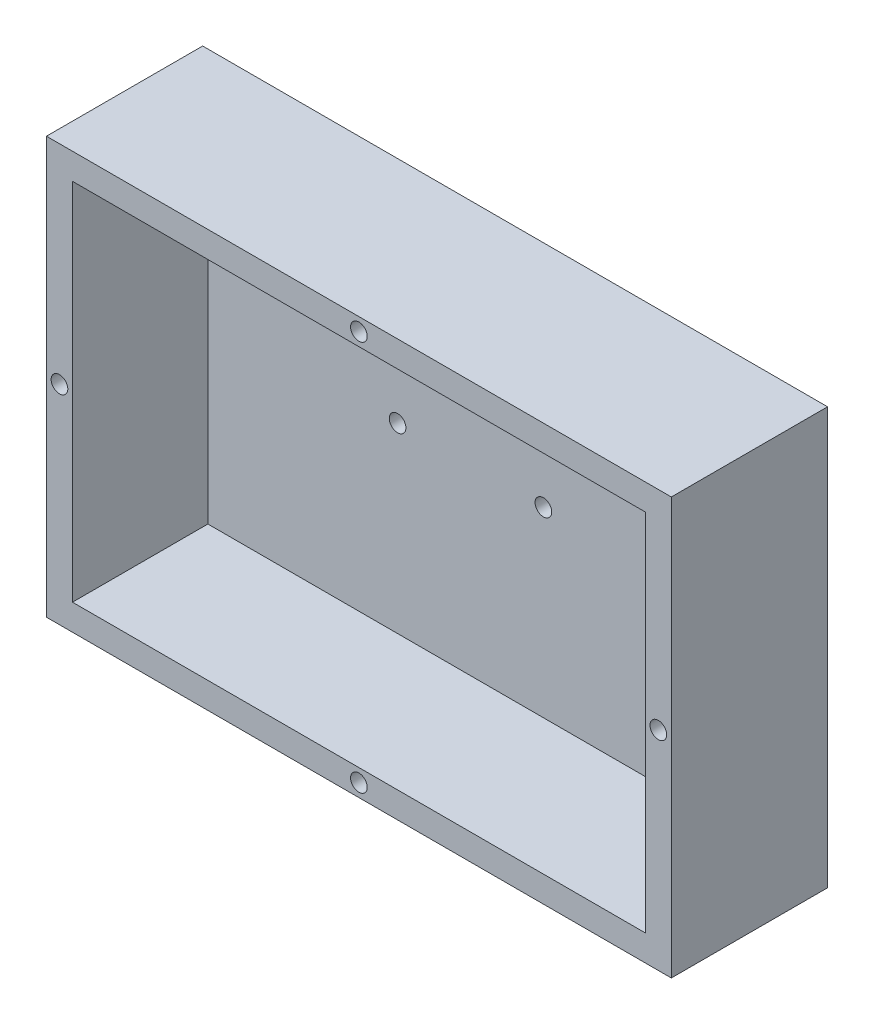
SolidWorks part; units mm, degrees
ref_plane "Front Plane" through (0, 0, 0) normal (0, 0, 1) x (1, 0, 0)
ref_plane "Top Plane" through (0, 0, 0) normal (0, 1, 0) x (1, 0, 0)
ref_plane "Right Plane" through (0, 0, 0) normal (1, 0, 0) x (0, 0, -1)
sketch "Sketch1" plane through (0, 0, 0) normal (0, 0, 1) x (1, 0, 0)
  line L1 (0, 0) -> (76.2, 0)
  line L2 (0, 0) -> (0, 50.8)
  line L3 (0, 50.8) -> (76.2, 50.8)
  line L4 (76.2, 0) -> (76.2, 50.8)
  dimension "D1" = 50.8
  dimension "D2" = 76.2
extrude "Boss-Extrude1" add sketch "Sketch1" along normal blind 19.05
sketch "Sketch2" plane through (0, 0, 19.05) normal (0, 0, 1) x (1, 0, 0)
  line L0 (38.1, 50.8) -> (38.1, 0)
  line L1 (76.2, 50.8) -> (0, 50.8) construction
  line L2 (0, 0) -> (76.2, 0) construction
  line L4 (3.175, 3.175) -> (73.025, 3.175)
  line L5 (3.175, 3.175) -> (3.175, 47.625)
  line L6 (3.175, 47.625) -> (73.025, 47.625)
  line L7 (73.025, 3.175) -> (73.025, 47.625)
  line L8 (3.175, 3.175) -> (73.025, 47.625) construction
  line L9 (3.175, 47.625) -> (73.025, 3.175) construction
  point P6 (38.1, 25.4)
  dimension "D1" = 44.45
  dimension "D2" = 69.85
extrude "Cut-Extrude1" cut sketch "Sketch2" against normal blind 16.51 contours L4 L7 L6 L0 | L6 L5 L4 L0
sketch "Sketch3" plane through (0, 0, 2.54) normal (0, 0, 1) x (1, 0, 0)
  line L0 (3.175, 25.4) -> (73.025, 25.4)
  line L1 (3.175, 3.175) -> (3.175, 47.625) construction
  line L2 (73.025, 3.175) -> (73.025, 47.625) construction
  line L3 (38.1, 47.625) -> (38.1, 3.175)
  line L6 (3.175, 47.625) -> (73.025, 47.625) construction
  line L7 (3.175, 3.175) -> (73.025, 3.175) construction
  circle A0 centre (26.31, 25.4) radius 3.175
  circle A1 centre (44.09, 25.4) radius 1.5875
  circle A2 centre (26.31, 25.4) radius 13.335
  circle A3 centre (44.09, 25.4) radius 5.334
  dimension "D1" = 6.35
  dimension "D2" = 3.175
  dimension "D3" = 26.67
  dimension "D4" = 10.668
  dimension "D5" = 17.78
sketch "Sketch4" plane through (0, 0, 19.05) normal (0, 0, 1) x (1, 0, 0)
  line L0 (38.1, 47.625) -> (38.1, 3.175) construction
  line L2 (3.175, 25.4) -> (73.025, 25.4) construction
  circle A0 centre (1.5875, 25.4) radius 1.016
  circle A1 centre (38.1, 49.2125) radius 1.016
  circle A2 centre (74.6125, 25.4) radius 1.016
  circle A3 centre (38.1, 1.5875) radius 1.016
  dimension "D1" = 2.032
  dimension "D2" = 2.032
  dimension "D3" = 2.032
  dimension "D4" = 2.032
extrude "Cut-Extrude4" cut sketch "Sketch4" against normal blind 5.08
sketch "Sketch6" plane through (0, 0, 2.54) normal (0, 0, 1) x (1, 0, 0)
  circle A0 centre (26.31, 25.4) radius 1.016
  circle A1 centre (44.09, 25.4) radius 1.016
  dimension "D1" = 2.032
  dimension "D2" = 2.032
extrude "Cut-Extrude6" cut sketch "Sketch6" against normal through all
